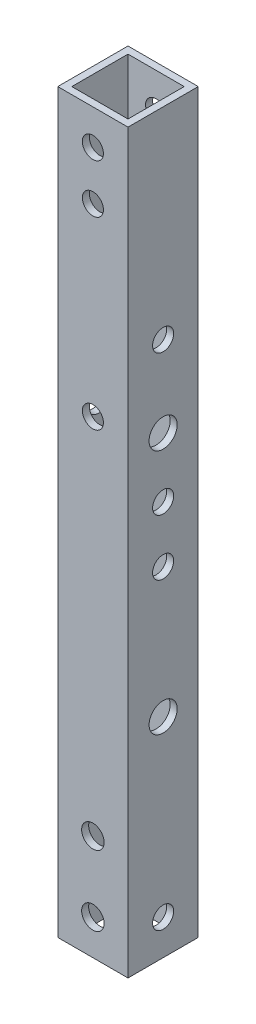
SolidWorks part; units mm, degrees
material "1060 合金"
ref_plane "正面" through (0, 0, 0) normal (0, 0, 1) x (1, 0, 0)
ref_plane "平面" through (0, 0, 0) normal (0, 1, 0) x (1, 0, 0)
ref_plane "右側面" through (0, 0, 0) normal (1, 0, 0) x (0, 0, -1)
sketch "ｽｹｯﾁ1" plane through (0, 0, 0) normal (0, 1, 0) x (1, 0, 0)
  line L1 (-5, -5) -> (5, -5)
  line L2 (-5, -5) -> (-5, 5)
  line L3 (-5, 5) -> (5, 5)
  line L4 (5, -5) -> (5, 5)
  line L5 (-5, -5) -> (5, 5) construction
  line L6 (-5, 5) -> (5, -5) construction
  point P0 (0, 0)
  dimension "D1" = 10
extrude "押し出し-薄板1" add sketch "ｽｹｯﾁ1" along normal blind 104.9 thin thin type one direction reverse wall 1
sketch "ｽｹｯﾁ2" plane through (0, 0, 5) normal (0, 0, 1) x (1, 0, 0)
  line L0 (0, 0) -> (0, 104.9) construction
  line L1 (-5, 104.9) -> (5, 104.9) construction
  line L2 (-5, 0) -> (5, 0) construction
  circle A1 centre (0, 5) radius 1.6
  circle A4 centre (0, 15) radius 1.6
  circle A5 centre (0, 92.95) radius 1.5
  circle A6 centre (0, 66.7) radius 1.5
  circle A7 centre (0, 99.9) radius 1.5
  dimension "D1" = 5
  dimension "D2" = 3.2
  dimension "D3" = 11.95
  dimension "D4" = 3
  dimension "D5" = 38.2
  dimension "D6" = 6.95
  dimension "D7" = 10
extrude "ｶｯﾄ - 押し出し1" cut sketch "ｽｹｯﾁ2" against normal through all
sketch "ｽｹｯﾁ3" plane through (5, 0, 0) normal (1, 0, 0) x (0, 0, -1)
  line L0 (0, 0) -> (0, 104.9) construction
  line L1 (-5, 0) -> (5, 0) construction
  line L2 (-5, 104.9) -> (5, 104.9) construction
  circle A15 centre (0, 76.2) radius 1.5
  circle A17 centre (0, 5) radius 1.5
  circle A18 centre (0, 64.7) radius 2
  circle A19 centre (0, 29.7) radius 2
  circle A20 centre (0, 48.2) radius 1.5
  circle A21 centre (0, 56.2) radius 1.5
  dimension "D2" = 24.7
  dimension "D3" = 35
  dimension "D4" = 11.5
  dimension "D5" = 3
  dimension "D6" = 4
  dimension "D7" = 48.2
  dimension "D8" = 8
  dimension "D9" = 3
  dimension "D11" = 5
  dimension "D12" = 3
extrude "ｶｯﾄ - 押し出し2" cut sketch "ｽｹｯﾁ3" against normal through all
